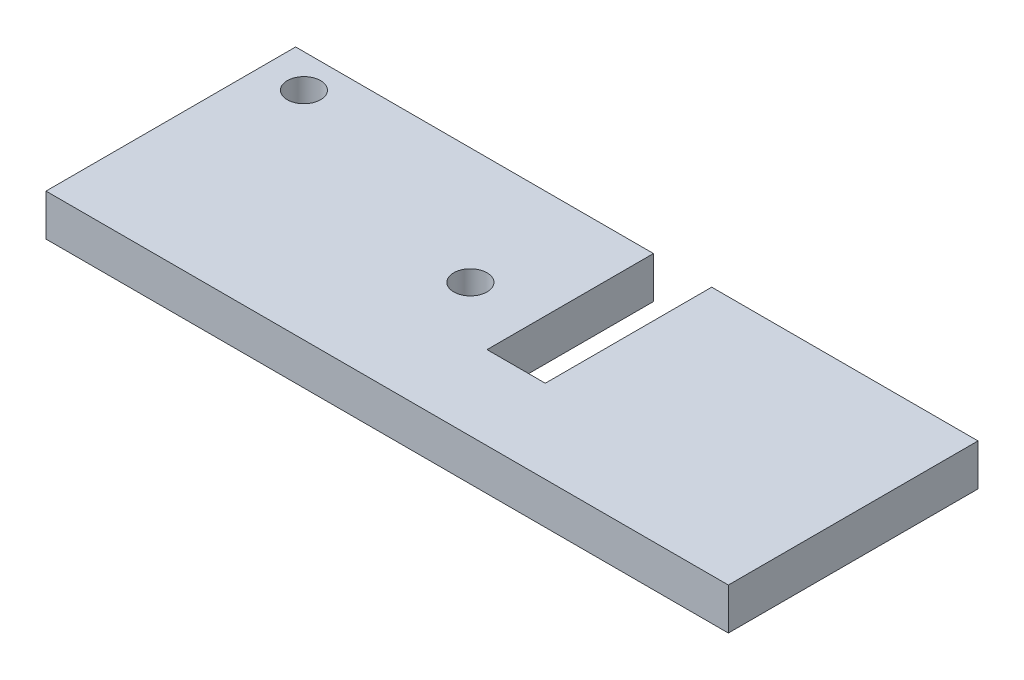
SolidWorks part; units mm, degrees
material "Acrylic"
ref_plane "Front Plane" through (0, 0, 0) normal (0, 0, 1) x (1, 0, 0)
ref_plane "Top Plane" through (0, 0, 0) normal (0, 1, 0) x (1, 0, 0)
ref_plane "Right Plane" through (0, 0, 0) normal (1, 0, 0) x (0, 0, -1)
sketch "Sketch1" plane through (0, 0, 0) normal (0, 1, 0) x (1, 0, 0)
  line L0 (50, 30) -> (82, 30)
  line L1 (0, 0) -> (82, 0)
  line L2 (0, 0) -> (0, 30)
  line L3 (0, 30) -> (43, 30)
  line L4 (82, 0) -> (82, 30)
  line L14 (43, 30) -> (43, 10)
  line L15 (43, 10) -> (50, 10)
  line L16 (50, 30) -> (50, 10)
  circle A0 centre (5, 26) radius 2
  circle A1 centre (35, 16) radius 2
  dimension "D8" = 4
  dimension "D10" = 30
  dimension "D1" = 82
  dimension "D2" = 7
  dimension "D3" = 43
  dimension "D4" = 30
  dimension "D5" = 20
  dimension "D6" = 4
  dimension "D7" = 5
  dimension "D9" = 10
extrude "Boss-Extrude1" add sketch "Sketch1" against normal blind 5
